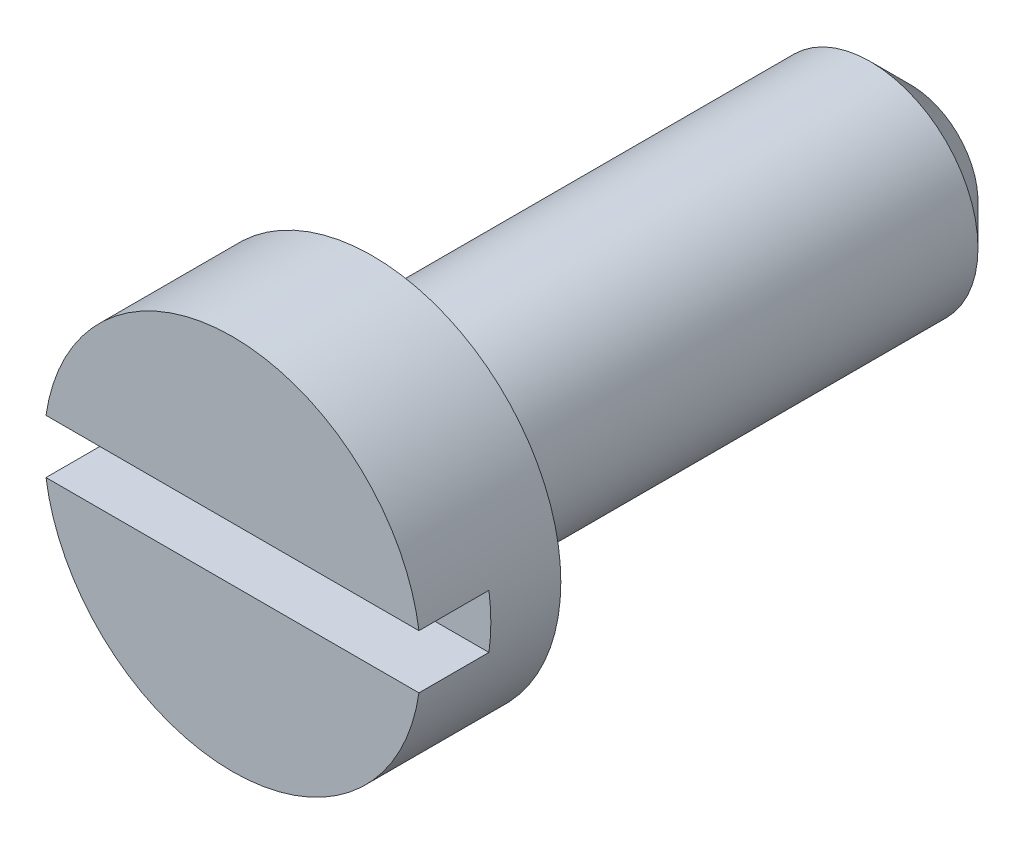
SolidWorks part; units mm, degrees
ref_plane "Спереди" through (0, 0, 0) normal (0, 0, 1) x (1, 0, 0)
ref_plane "Сверху" through (0, 0, 0) normal (0, 1, 0) x (1, 0, 0)
ref_plane "Справа" through (0, 0, 0) normal (1, 0, 0) x (0, 0, -1)
sketch "Эскиз12" plane through (0, 0, 0) normal (0, 0, 1) x (1, 0, 0)
  circle A0 centre (0, 0) radius 3.5
extrude "Вытянуть3" add sketch "Эскиз12" along normal blind 2.6
sketch "Эскиз13" plane through (0, 0, 0) normal (0, 0, -1) x (-1, 0, 0)
  circle A0 centre (0, 0) radius 2
extrude "Вытянуть4" add sketch "Эскиз13" along normal blind 10
sketch "Эскиз14" plane through (0, 0, 2.6) normal (0, 0, 1) x (1, 0, 0)
  line L0 (-3.5, 0) -> (3.5, 0) construction
  circle A0 centre (0, 0) radius 3.5 construction
sketch "Эскиз20" plane through (0, 0, 2.6) normal (0, 0, 1) x (1, 0, 0)
  line L0 (-3.5, 0) -> (3.5, 0) construction
  line L1 (-4.098, 0.5) -> (3.9902, 0.5)
  line L2 (-4.098, 0.5) -> (-4.098, -0.5)
  line L3 (-4.098, -0.5) -> (3.9902, -0.5)
  line L4 (3.9902, 0.5) -> (3.9902, -0.5)
  dimension "D1" = 0.5
  dimension "D2" = 0.5
extrude "Вырез-Вытянуть8" cut sketch "Эскиз20" against normal blind 1.3
chamfer "Фаска1" distance 0.75 angle 45 1 edges at (-2, 0, -10)
